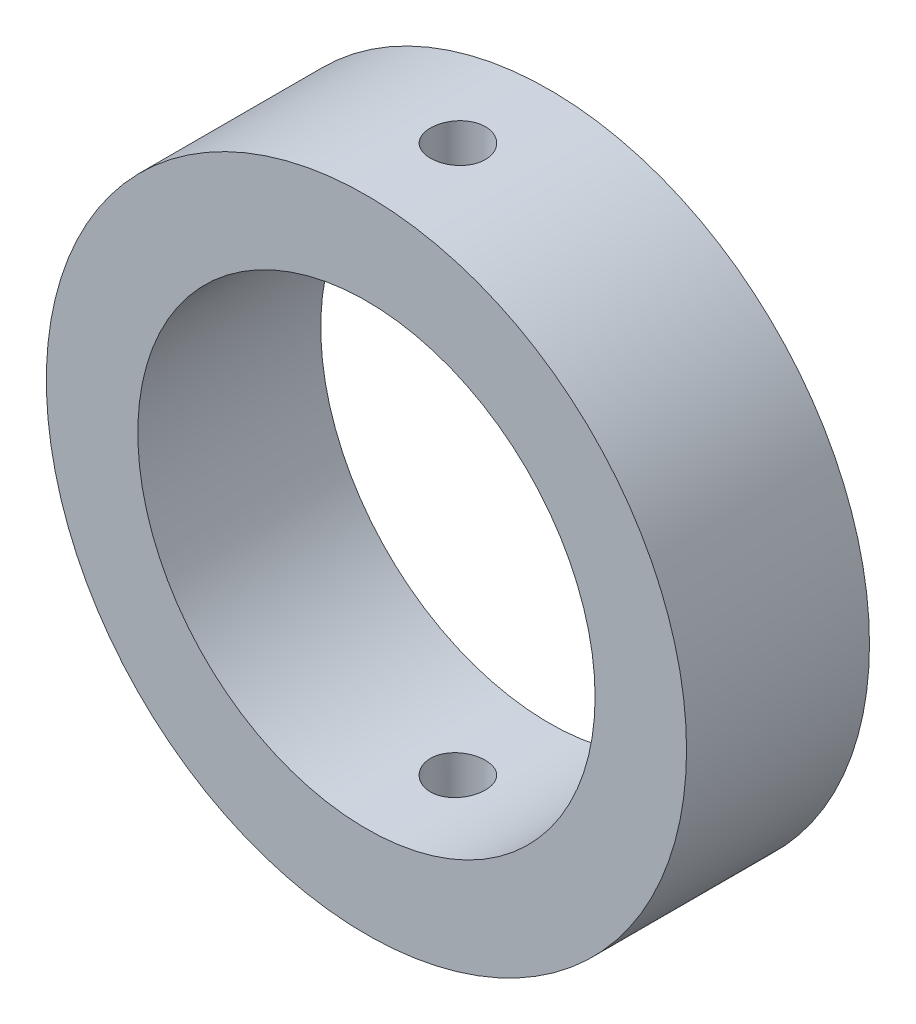
SolidWorks part; units mm, degrees
ref_plane "Front Plane" through (0, 0, 0) normal (0, 0, 1) x (1, 0, 0)
ref_plane "Top Plane" through (0, 0, 0) normal (0, 1, 0) x (1, 0, 0)
ref_plane "Right Plane" through (0, 0, 0) normal (1, 0, 0) x (0, 0, -1)
sketch "Sketch1" plane through (0, 0, 0) normal (0, 0, 1) x (1, 0, 0)
  circle A0 centre (0, 0) radius 250
  circle A1 centre (0, 0) radius 350
  dimension "D1" = 500
  dimension "D2" = 700
extrude "Boss-Extrude1" add sketch "Sketch1" along normal blind 200
sketch "Sketch2" plane through (0, 0, 0) normal (0, 1, 0) x (1, 0, 0)
  line L0 (350, 0) -> (-350, 0) construction
  circle A0 centre (0, -100) radius 30
  dimension "D1" = 60
  dimension "D2" = 100
extrude "Cut-Extrude1" cut sketch "Sketch2" against normal through all both and the other way through all
